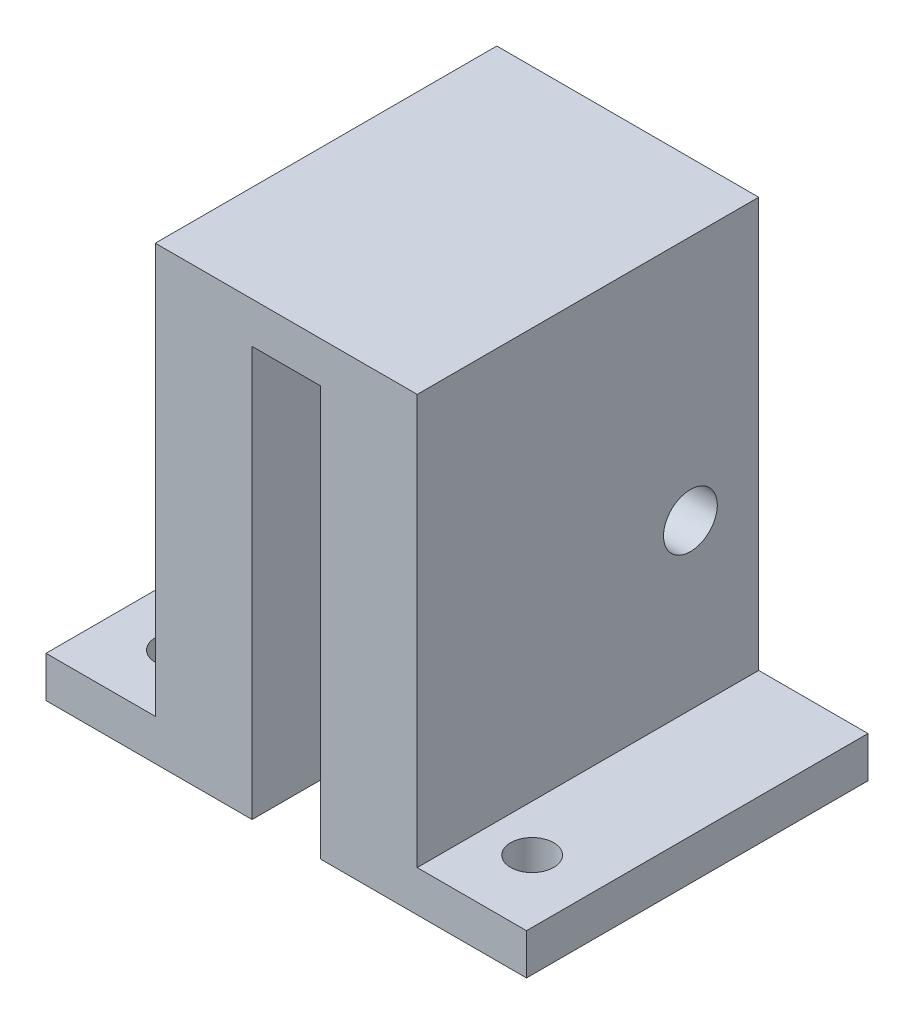
SolidWorks part; units mm, degrees
ref_plane "Front Plane" through (0, 0, 0) normal (0, 0, 1) x (1, 0, 0)
ref_plane "Top Plane" through (0, 0, 0) normal (0, 1, 0) x (1, 0, 0)
ref_plane "Right Plane" through (0, 0, 0) normal (1, 0, 0) x (0, 0, -1)
sketch "Sketch1" plane through (0, 0, 0) normal (0, 0, 1) x (1, 0, 0)
  line L0 (-3.175, 0) -> (3.175, 0)
  line L1 (3.175, 0) -> (3.175, -38.1)
  line L2 (3.175, -38.1) -> (22.335, -38.1)
  line L4 (12.175, 3.81) -> (-12.175, 3.81)
  line L6 (-22.335, -38.1) -> (-3.175, -38.1)
  line L7 (-3.175, -38.1) -> (-3.175, 0)
  line L8 (22.335, -38.1) -> (22.335, -34.29)
  line L9 (22.335, -34.29) -> (12.175, -34.29)
  line L10 (12.175, -34.29) -> (12.175, 3.81)
  line L11 (-12.175, 3.81) -> (-12.175, -34.29)
  line L12 (-12.175, -34.29) -> (-22.335, -34.29)
  line L13 (-22.335, -34.29) -> (-22.335, -38.1)
  line L14 (0, 0) -> (0, 3.81) construction
  dimension "D1" = 6.35
  dimension "D2" = 38.1
  dimension "D3" = 3.81
  dimension "D4" = 9
  dimension "D5" = 3.81
  dimension "D6" = 10.16
extrude "Boss-Extrude1" add sketch "Sketch1" along normal blind 31.75
sketch "Sketch2" plane through (0, -38.1, 0) normal (0, -1, 0) x (1, 0, 0)
  line L1 (3.175, 31.75) -> (22.335, 31.75) construction
  line L2 (0, 31.75) -> (0, 0) construction
  line L3 (-3.175, 31.75) -> (3.175, 31.75) construction
  circle A0 centre (16.51, 25.4) radius 2
  circle A1 centre (-16.51, 25.4) radius 2
  dimension "D1" = 4
  dimension "D2" = 33.02
  dimension "D3" = 6.35
extrude "Cut-Extrude1" cut sketch "Sketch2" against normal through all contours A1 | A0
sketch "Sketch3" plane through (-12.175, 0, 0) normal (-1, 0, 0) x (0, 0, 1)
  line L1 (4.15, -20.4356) -> (8.55, -20.4356)
  line L2 (4.15, -20.4356) -> (4.15, -17.6644)
  line L3 (4.15, -17.6644) -> (8.55, -17.6644)
  line L4 (8.55, -20.4356) -> (8.55, -17.6644)
  line L5 (4.15, -20.4356) -> (8.55, -17.6644) construction
  line L6 (4.15, -17.6644) -> (8.55, -20.4356) construction
  line L8 (0, 3.81) -> (0, -34.29) construction
  line L9 (31.75, -34.29) -> (0, -34.29) construction
  line L10 (4.15, -17.6644) -> (8.55, -17.6644)
  arc A1 (4.15, -17.6644) -> (8.55, -17.6644) centre (6.35, -19.05) cw
  arc A2 (4.15, -20.4356) -> (8.55, -20.4356) centre (6.35, -19.05) ccw
  point P6 (6.35, -16.45)
  point P7 (6.35, -21.65)
  dimension "D1" = 5.2
  dimension "D2" = 4.4
  dimension "D3" = 6.35
  dimension "D4" = 15.24
extrude "Cut-Extrude2" cut sketch "Sketch3" against normal up to next contours L2 L1 L4 L3
sketch "Sketch4" plane through (-12.175, 0, 0) normal (-1, 0, 0) x (0, 0, 1)
  line L1 (4.15, -20.4356) -> (8.55, -20.4356) construction
  line L2 (4.15, -20.4356) -> (4.15, -17.6644)
  line L3 (4.15, -17.6644) -> (8.55, -17.6644) construction
  line L4 (8.55, -20.4356) -> (8.55, -17.6644)
  line L5 (4.15, -20.4356) -> (8.55, -17.6644) construction
  line L6 (4.15, -17.6644) -> (8.55, -20.4356) construction
  arc A1 (4.15, -17.6644) -> (8.55, -17.6644) centre (6.35, -19.05) cw
  arc A2 (4.15, -20.4356) -> (8.55, -20.4356) centre (6.35, -19.05) ccw
  point P3 (6.35, -19.05)
extrude "Cut-Extrude3" cut sketch "Sketch4" against normal up to next
sketch "Sketch5" plane through (12.175, 0, 0) normal (1, 0, 0) x (0, 0, -1)
  circle A0 centre (-6.35, -19.05) radius 2.5
  arc A1 (-4.15, -17.6644) -> (-8.55, -17.6644) centre (-6.35, -19.05) ccw construction
  dimension "D1" = 5
extrude "Cut-Extrude4" cut sketch "Sketch5" against normal up to next
